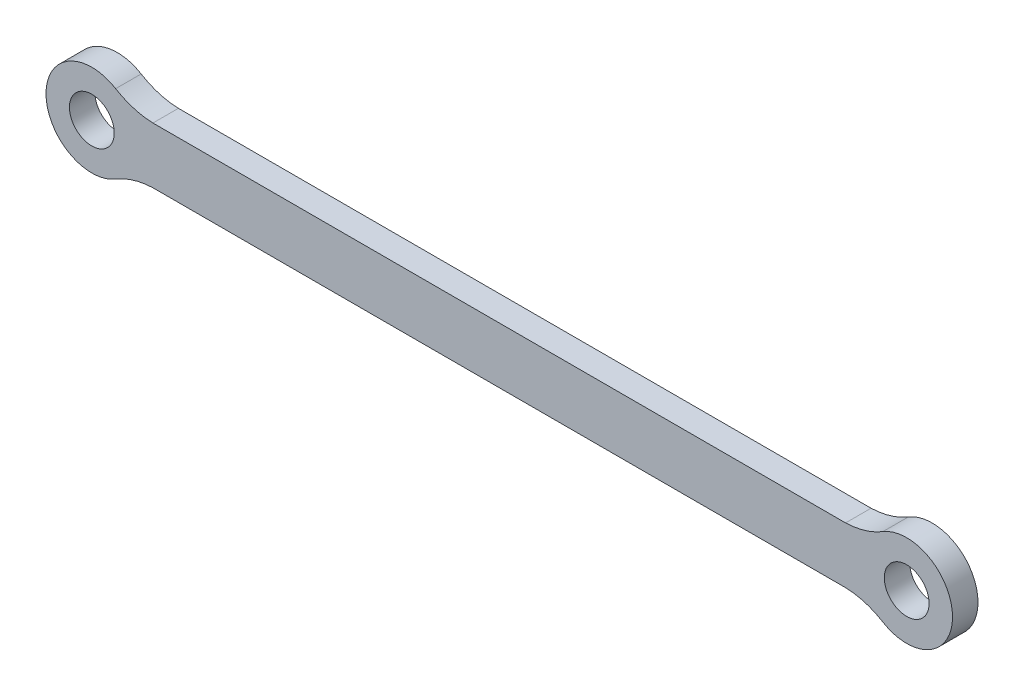
SolidWorks part; units mm, degrees
ref_plane "Plan de face" through (0, 0, 0) normal (0, 0, 1) x (1, 0, 0)
ref_plane "Plan de dessus" through (0, 0, 0) normal (0, 1, 0) x (1, 0, 0)
ref_plane "Plan de droite" through (0, 0, 0) normal (1, 0, 0) x (0, 0, -1)
sketch "Esquisse1" plane through (0, 0, 0) normal (0, 0, 1) x (1, 0, 0)
  line L0 (68, 5.5076) -> (-68, 5.5076)
  line L1 (-68, -5.5076) -> (68, -5.5076)
  line L2 (-80, 0) -> (80, 0) construction
  arc A0 (-68, -5.5076) -> (-75.32, -7.6875) centre (-67.5199, -20.5) ccw
  arc A1 (-75.32, 7.6875) -> (-75.32, -7.6875) centre (-80, 0) ccw
  arc A3 (-75.32, 7.6875) -> (-68, 5.5076) centre (-67.5199, 20.5) ccw
  arc A4 (68, 5.5076) -> (75.32, 7.6875) centre (67.5199, 20.5) ccw
  arc A6 (75.32, -7.6875) -> (75.32, 7.6875) centre (80, 0) ccw
  arc A7 (75.32, -7.6875) -> (68, -5.5076) centre (67.5199, -20.5) ccw
  circle A8 centre (-80, 0) radius 4.4
  circle A9 centre (80, 0) radius 4.4
  dimension "D1" = 15
  dimension "D2" = 8.8
  dimension "D3" = 9
  dimension "D4" = 160
  dimension "D5" = 68
  dimension "D6" = 68
extrude "Boss.-Extru.1" add sketch "Esquisse1" along normal blind 5
